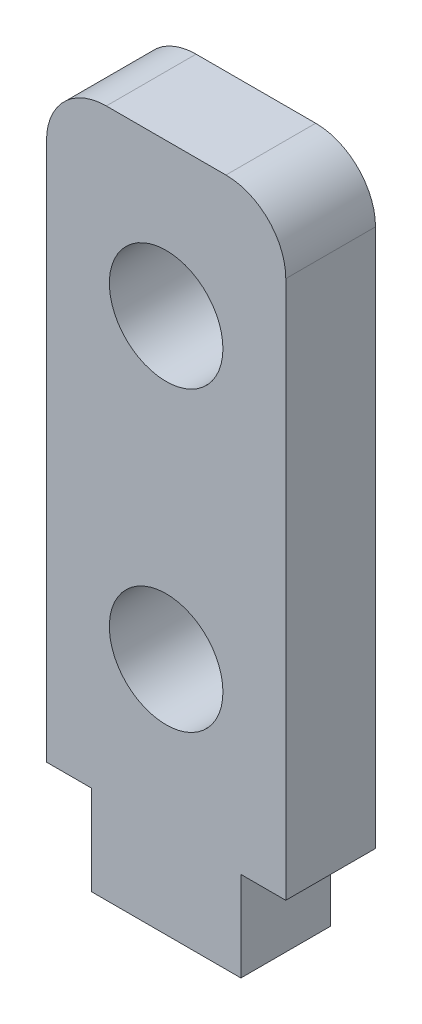
SolidWorks part; units mm, degrees
material "Acrylic (Medium-high impact)"
ref_plane "Front Plane" through (0, 0, 0) normal (0, 0, 1) x (1, 0, 0)
ref_plane "Top Plane" through (0, 0, 0) normal (0, 1, 0) x (1, 0, 0)
ref_plane "Right Plane" through (0, 0, 0) normal (1, 0, 0) x (0, 0, -1)
sketch "Sketch1" plane through (0, 0, 0) normal (0, 0, 1) x (1, 0, 0)
  line L1 (-4, 23) -> (4, 23)
  line L2 (-4, 23) -> (-4, 3)
  line L3 (-4, 3) -> (4, 3)
  line L4 (4, 23) -> (4, 3)
  line L5 (-2.5, 3) -> (2.5, 3)
  line L6 (-2.5, 3) -> (-2.5, 0)
  line L7 (-2.5, 0) -> (2.5, 0)
  line L8 (2.5, 3) -> (2.5, 0)
  point P8 (0, 0)
  point P9 (0, 3)
  dimension "D1" = 5
  dimension "D2" = 3
  dimension "D3" = 8
  dimension "D4" = 20
extrude "Boss-Extrude1" add sketch "Sketch1" along normal blind 3 contours L4 L1 L2 L3 | L8 L3 L6 L7
hole_wizard "#6 Clearance Hole1" positions "Sketch2" profile "Sketch3" hole size "#6" standard "ANSI Inch" end condition through all
sketch "Sketch2" plane through (0, 0, 3) normal (0, 0, 1) x (1, 0, 0)
  point P0 (0, 17.92)
  point P2 (0, 7.98)
  dimension "D1" = 9.94
  dimension "D2" = 7.98
sketch "Sketch3" plane through (0, 17.92, 3) normal (1, 0, 0) x (0, -1, 0)
  line L0 (0, 0) -> (0, 3)
  line L1 (0, 3) -> (1.8986, 3)
  line L2 (1.8986, 3) -> (1.8986, 0)
  line L5 (1.8986, 0) -> (0, 0)
  line L11 (0, -6.35) -> (0, 107.95) construction
  dimension "Thru Hole Dia." = 3.7973
  dimension "Thru Hole Depth" = 3
fillet "Fillet1" radius 2 2 edges at (-4, 23, 1.5) (4, 23, 1.5)
